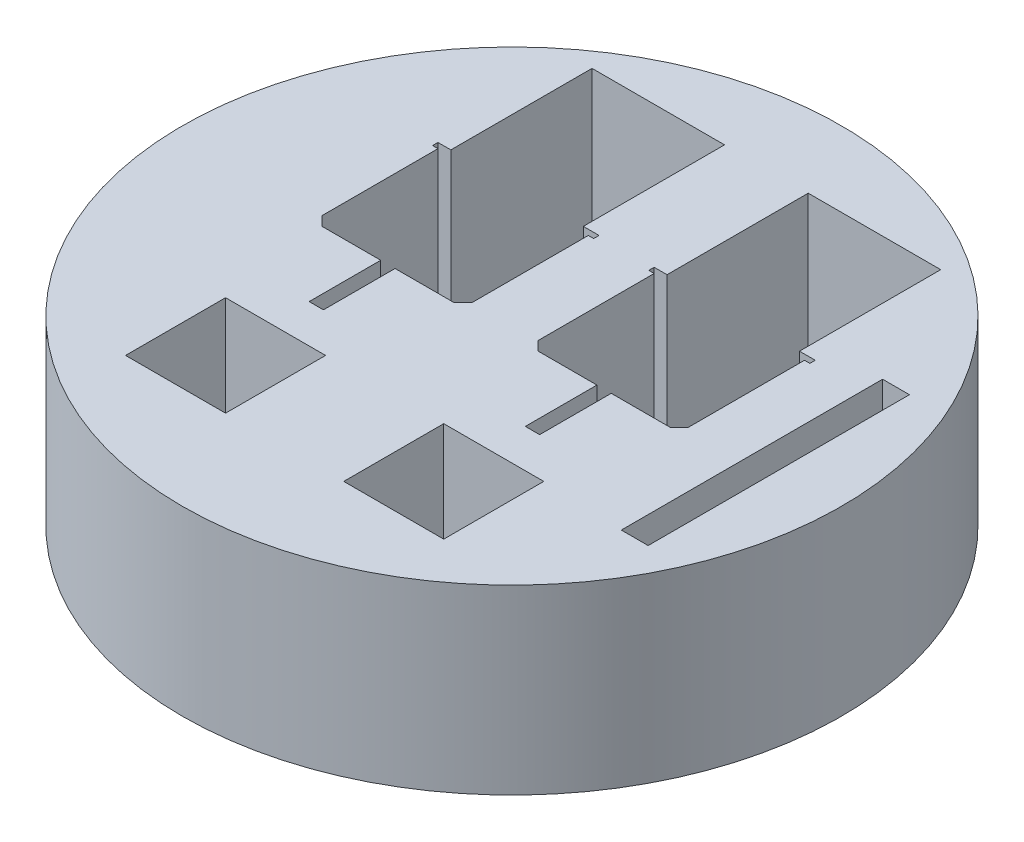
SolidWorks part; units mm, degrees
material "Polyurethane Foam Flexible"
ref_plane "Front Plane" through (0, 0, 0) normal (0, 0, 1) x (1, 0, 0)
ref_plane "Top Plane" through (0, 0, 0) normal (0, 1, 0) x (1, 0, 0)
ref_plane "Right Plane" through (0, 0, 0) normal (1, 0, 0) x (0, 0, -1)
sketch "Sketch1" plane through (0, 0, 0) normal (0, 1, 0) x (1, 0, 0)
  circle A0 centre (0, 0) radius 92.075
  dimension "D1" = 184.15
extrude "Boss-Extrude1" add sketch "Sketch1" along normal blind 50.8
sketch "Sketch4" plane through (0, 0, 0) normal (0, 1, 0) x (1, 0, 0)
  line L0 (0, 0) -> (0, 16.6464) construction
  line L1 (-55.88, 71.12) -> (-5.08, 71.12)
  line L2 (-55.88, 71.12) -> (-55.88, -25.4)
  line L3 (-55.88, -25.4) -> (-5.08, -25.4)
  line L4 (-5.08, 71.12) -> (-5.08, -25.4)
  line L5 (55.88, 71.12) -> (5.08, 71.12)
  line L6 (5.08, 71.12) -> (5.08, -25.4)
  line L7 (55.88, -25.4) -> (5.08, -25.4)
  line L8 (55.88, 71.12) -> (55.88, -25.4)
  dimension "D1" = 5.08
  dimension "D2" = 96.52
  dimension "D3" = 71.12
  dimension "D4" = 50.8
extrude "Cut-Extrude3" [suppressed] cut sketch "Sketch4" along normal up to surface (50.8 mm away)
sketch "Sketch6" plane through (0, 0, 0) normal (0, -1, 0) x (1, 0, 0)
  line L1 (-44.45, -63.5) -> (-16.51, -63.5) construction
  line L2 (-44.45, -63.5) -> (-44.45, -35.56) construction
  line L3 (-44.45, -35.56) -> (-16.51, -35.56) construction
  line L4 (-16.51, -63.5) -> (-16.51, -35.56) construction
  line L5 (0, 0) -> (0, -11.8444) construction
  line L6 (44.45, -63.5) -> (44.45, -35.56) construction
  line L7 (44.45, -63.5) -> (16.51, -63.5) construction
  line L8 (16.51, -63.5) -> (16.51, -35.56) construction
  line L9 (44.45, -35.56) -> (16.51, -35.56) construction
  line L10 (0, 0) -> (-75.2732, 0) construction
  line L11 (44.45, 63.5) -> (16.51, 63.5)
  line L12 (44.45, 63.5) -> (44.45, 35.56)
  line L13 (-44.45, 35.56) -> (-16.51, 35.56)
  line L14 (44.45, 35.56) -> (16.51, 35.56)
  line L15 (16.51, 63.5) -> (16.51, 35.56)
  line L16 (-16.51, 63.5) -> (-16.51, 35.56)
  line L17 (-44.45, 63.5) -> (-16.51, 63.5)
  line L18 (-44.45, 63.5) -> (-44.45, 35.56)
  dimension "D1" = 27.94
  dimension "D2" = 27.94
  dimension "D3" = 35.56
  dimension "D4" = 16.51
extrude "Cut-Extrude4" cut sketch "Sketch6" against normal up to surface (50.8 mm away) up to face at (0, 50.8, 92.075)
sketch "Sketch8" plane through (0, 50.8, 0) normal (0, 1, 0) x (1, 0, 0)
  line L0 (48.6732, 66.9206) -> (48.6732, 31.675)
  line L1 (48.6732, 31.675) -> (53.066, 31.675)
  line L2 (53.066, 31.675) -> (53.066, 30.175)
  line L3 (53.066, 30.175) -> (51.5683, 30.175)
  line L4 (51.5683, 30.175) -> (51.5683, -2.285)
  line L5 (51.5683, -2.285) -> (49.0283, -4.825)
  line L6 (49.0283, -4.825) -> (32.5683, -4.825)
  line L7 (32.5683, -4.825) -> (32.5683, -24.825)
  line L8 (32.5683, -24.825) -> (28.5683, -24.825)
  line L9 (28.5683, -24.825) -> (28.5683, -4.825)
  line L10 (28.5683, -4.825) -> (12.1083, -4.825)
  line L11 (12.1083, -4.825) -> (9.5683, -2.285)
  line L12 (9.5683, -2.285) -> (9.5683, 30.175)
  line L13 (9.5683, 30.175) -> (8.066, 30.175)
  line L14 (8.066, 30.175) -> (8.066, 31.675)
  line L15 (8.066, 31.675) -> (10.8383, 31.675)
  line L16 (11.6589, 66.9206) -> (11.6589, 31.675)
  line L17 (11.6589, 31.675) -> (10.8383, 31.675)
  line L18 (11.6589, 66.9206) -> (11.6589, 71.12)
  line L20 (11.6589, 71.12) -> (48.6732, 71.12)
  line L21 (48.6732, 71.12) -> (48.6732, 66.9206)
  line L22 (-8.8317, -2.285) -> (-11.3717, -4.825)
  line L23 (-11.3717, -4.825) -> (-27.8317, -4.825)
  line L24 (-27.8317, -4.825) -> (-27.8317, -24.825)
  line L25 (-27.8317, -24.825) -> (-31.8317, -24.825)
  line L26 (-31.8317, -24.825) -> (-31.8317, -4.825)
  line L27 (-31.8317, -4.825) -> (-48.2917, -4.825)
  line L28 (-48.2917, -4.825) -> (-50.8317, -2.285)
  line L29 (-50.8317, -2.285) -> (-50.8317, 30.175)
  line L30 (-50.8317, 30.175) -> (-52.334, 30.175)
  line L31 (-52.334, 30.175) -> (-52.334, 31.675)
  line L32 (-52.334, 31.675) -> (-48.7411, 31.675)
  line L33 (-48.7411, 66.9206) -> (-48.7411, 31.675)
  line L34 (-8.8317, -2.285) -> (-8.8317, 30.175)
  line L35 (-8.8317, 30.175) -> (-7.334, 30.175)
  line L36 (-7.334, 30.175) -> (-7.334, 31.675)
  line L37 (-11.7268, 66.9206) -> (-11.7268, 31.675)
  line L38 (-11.7268, 31.675) -> (-7.334, 31.675)
  line L39 (-11.7268, 66.9206) -> (-11.7268, 71.12)
  line L41 (-11.7268, 71.12) -> (-48.7411, 71.12)
  line L42 (-48.7411, 71.12) -> (-48.7411, 66.9206)
extrude "Cut-Extrude5" cut sketch "Sketch8" against normal up to surface (50.8 mm away) up to face at (-30.48, 0, 49.53)
sketch "Sketch9" plane through (0, 50.8, 0) normal (0, 1, 0) x (1, 0, 0)
  line L0 (0, 0) -> (-67.31, 0) construction
  line L1 (-74.81, 36.5) -> (-67.31, 36.5)
  line L2 (-74.81, 36.5) -> (-74.81, -36.5)
  line L3 (-74.81, -36.5) -> (-67.31, -36.5)
  line L4 (-67.31, 36.5) -> (-67.31, -36.5)
  point P7 (-67.31, 0)
  dimension "D1" = 73
  dimension "D2" = 7.5
  dimension "D3" = 67.31
extrude "Cut-Extrude6" [suppressed] cut sketch "Sketch9" against normal up to surface (50.8 mm away)
sketch "Sketch10" plane through (0, 50.8, 0) normal (0, 1, 0) x (1, 0, 0)
  line L0 (0, 0) -> (67.056, 0) construction
  line L1 (67.056, 36.5) -> (74.556, 36.5)
  line L2 (67.056, 36.5) -> (67.056, -36.5)
  line L3 (67.056, -36.5) -> (74.556, -36.5)
  line L4 (74.556, 36.5) -> (74.556, -36.5)
  point P7 (67.056, 0)
  point P8 (67.056, 0)
  dimension "D1" = 67.056
  dimension "D2" = 7.5
  dimension "D3" = 73
extrude "Cut-Extrude7" cut sketch "Sketch10" against normal blind 15.24
